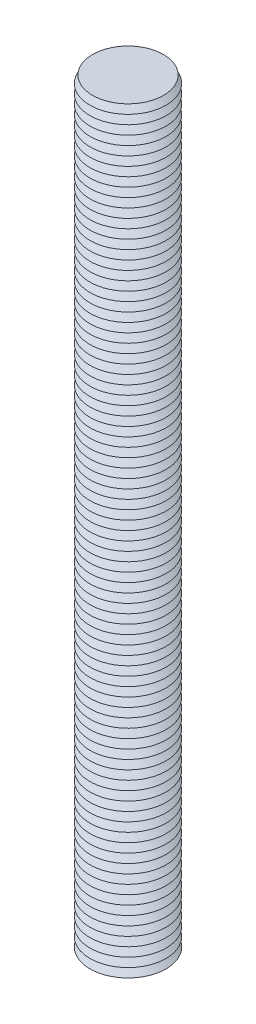
SolidWorks part; units mm, degrees
ref_plane "前视基准面" through (0, 0, 0) normal (0, 0, 1) x (1, 0, 0)
ref_plane "上视基准面" through (0, 0, 0) normal (0, 1, 0) x (1, 0, 0)
ref_plane "右视基准面" through (0, 0, 0) normal (1, 0, 0) x (0, 0, -1)
sketch "草图1" plane through (0, 0, 0) normal (0, 0, 1) x (1, 0, 0)
  line B0 (0, 0) -> (0, 80)
  line B1 (3.3, 0) -> (0, 0)
  line B2 (4, 0.4744) -> (3.3, 0)
  line B3 (0, 80) -> (3.7341, 80)
  line B4 (4, 0.4744) -> (3.3, 0.9489)
  line B5 (4, 1.4233) -> (3.3, 0.9489)
  line B6 (4, 1.4233) -> (3.3, 1.8978)
  line B7 (4, 2.3722) -> (3.3, 1.8978)
  line B8 (4, 2.3722) -> (3.3, 2.8466)
  line B9 (4, 3.3211) -> (3.3, 2.8466)
  line B10 (4, 3.3211) -> (3.3, 3.7955)
  line B11 (4, 4.27) -> (3.3, 3.7955)
  line B12 (4, 4.27) -> (3.3, 4.7444)
  line B13 (4, 5.2188) -> (3.3, 4.7444)
  line B14 (4, 5.2188) -> (3.3, 5.6933)
  line B15 (4, 6.1677) -> (3.3, 5.6933)
  line B16 (4, 6.1677) -> (3.3, 6.6421)
  line B17 (4, 7.1166) -> (3.3, 6.6421)
  line B18 (4, 7.1166) -> (3.3, 7.591)
  line B19 (4, 8.0655) -> (3.3, 7.591)
  line B20 (4, 8.0655) -> (3.3, 8.5399)
  line B21 (4, 9.0143) -> (3.3, 8.5399)
  line B22 (4, 9.0143) -> (3.3, 9.4888)
  line B23 (4, 9.9632) -> (3.3, 9.4888)
  line B24 (4, 9.9632) -> (3.3, 10.4377)
  line B25 (4, 10.9121) -> (3.3, 10.4377)
  line B26 (4, 10.9121) -> (3.3, 11.3865)
  line B27 (4, 11.861) -> (3.3, 11.3865)
  line B28 (4, 11.861) -> (3.3, 12.3354)
  line B29 (4, 12.8099) -> (3.3, 12.3354)
  line B30 (4, 12.8099) -> (3.3, 13.2843)
  line B31 (4, 13.7587) -> (3.3, 13.2843)
  line B32 (4, 13.7587) -> (3.3, 14.2332)
  line B33 (4, 14.7076) -> (3.3, 14.2332)
  line B34 (4, 14.7076) -> (3.3, 15.1821)
  line B35 (4, 15.6565) -> (3.3, 15.1821)
  line B36 (4, 15.6565) -> (3.3, 16.1309)
  line B37 (4, 16.6054) -> (3.3, 16.1309)
  line B38 (4, 16.6054) -> (3.3, 17.0798)
  line B39 (4, 17.5542) -> (3.3, 17.0798)
  line B40 (4, 17.5542) -> (3.3, 18.0287)
  line B41 (4, 18.5031) -> (3.3, 18.0287)
  line B42 (4, 18.5031) -> (3.3, 18.9776)
  line B43 (4, 19.452) -> (3.3, 18.9776)
  line B44 (4, 19.452) -> (3.3, 19.9264)
  line B45 (4, 20.4009) -> (3.3, 19.9264)
  line B46 (4, 20.4009) -> (3.3, 20.8753)
  line B47 (4, 21.3498) -> (3.3, 20.8753)
  line B48 (4, 21.3498) -> (3.3, 21.8242)
  line B49 (4, 22.2986) -> (3.3, 21.8242)
  line B50 (4, 22.2986) -> (3.3, 22.7731)
  line B51 (4, 23.2475) -> (3.3, 22.7731)
  line B52 (4, 23.2475) -> (3.3, 23.722)
  line B53 (4, 24.1964) -> (3.3, 23.722)
  line B54 (4, 24.1964) -> (3.3, 24.6708)
  line B55 (4, 25.1453) -> (3.3, 24.6708)
  line B56 (4, 25.1453) -> (3.3, 25.6197)
  line B57 (4, 26.0942) -> (3.3, 25.6197)
  line B58 (4, 26.0942) -> (3.3, 26.5686)
  line B59 (4, 27.043) -> (3.3, 26.5686)
  line B60 (4, 27.043) -> (3.3, 27.5175)
  line B61 (4, 27.9919) -> (3.3, 27.5175)
  line B62 (4, 27.9919) -> (3.3, 28.4663)
  line B63 (4, 28.9408) -> (3.3, 28.4663)
  line B64 (4, 28.9408) -> (3.3, 29.4152)
  line B65 (4, 29.8897) -> (3.3, 29.4152)
  line B66 (4, 29.8897) -> (3.3, 30.3641)
  line B67 (4, 30.8385) -> (3.3, 30.3641)
  line B68 (4, 30.8385) -> (3.3, 31.313)
  line B69 (4, 31.7874) -> (3.3, 31.313)
  line B70 (4, 31.7874) -> (3.3, 32.2619)
  line B71 (4, 32.7363) -> (3.3, 32.2619)
  line B72 (4, 32.7363) -> (3.3, 33.2107)
  line B73 (4, 33.6852) -> (3.3, 33.2107)
  line B74 (4, 33.6852) -> (3.3, 34.1596)
  line B75 (4, 34.6341) -> (3.3, 34.1596)
  line B76 (4, 34.6341) -> (3.3, 35.1085)
  line B77 (4, 35.5829) -> (3.3, 35.1085)
  line B78 (4, 35.5829) -> (3.3, 36.0574)
  line B79 (4, 36.5318) -> (3.3, 36.0574)
  line B80 (4, 36.5318) -> (3.3, 37.0063)
  line B81 (4, 37.4807) -> (3.3, 37.0063)
  line B82 (4, 37.4807) -> (3.3, 37.9551)
  line B83 (4, 38.4296) -> (3.3, 37.9551)
  line B84 (4, 38.4296) -> (3.3, 38.904)
  line B85 (4, 39.3785) -> (3.3, 38.904)
  line B86 (4, 39.3785) -> (3.3, 39.8529)
  line B87 (4, 40.3273) -> (3.3, 39.8529)
  line B88 (4, 40.3273) -> (3.3, 40.8018)
  line B89 (4, 41.2762) -> (3.3, 40.8018)
  line B90 (4, 41.2762) -> (3.3, 41.7506)
  line B91 (4, 42.2251) -> (3.3, 41.7506)
  line B92 (4, 42.2251) -> (3.3, 42.6995)
  line B93 (4, 43.174) -> (3.3, 42.6995)
  line B94 (4, 43.174) -> (3.3, 43.6484)
  line B95 (4, 44.1228) -> (3.3, 43.6484)
  line B96 (4, 44.1228) -> (3.3, 44.5973)
  line B97 (4, 45.0717) -> (3.3, 44.5973)
  line B98 (4, 45.0717) -> (3.3, 45.5462)
  line B99 (4, 46.0206) -> (3.3, 45.5462)
  line B100 (4, 46.0206) -> (3.3, 46.495)
  line B101 (4, 46.9695) -> (3.3, 46.495)
  line B102 (4, 46.9695) -> (3.3, 47.4439)
  line B103 (4, 47.9184) -> (3.3, 47.4439)
  line B104 (4, 47.9184) -> (3.3, 48.3928)
  line B105 (4, 48.8672) -> (3.3, 48.3928)
  line B106 (4, 48.8672) -> (3.3, 49.3417)
  line B107 (4, 49.8161) -> (3.3, 49.3417)
  line B108 (4, 49.8161) -> (3.3, 50.2906)
  line B109 (4, 50.765) -> (3.3, 50.2906)
  line B110 (4, 50.765) -> (3.3, 51.2394)
  line B111 (4, 51.7139) -> (3.3, 51.2394)
  line B112 (4, 51.7139) -> (3.3, 52.1883)
  line B113 (4, 52.6627) -> (3.3, 52.1883)
  line B114 (4, 52.6627) -> (3.3, 53.1372)
  line B115 (4, 53.6116) -> (3.3, 53.1372)
  line B116 (4, 53.6116) -> (3.3, 54.0861)
  line B117 (4, 54.5605) -> (3.3, 54.0861)
  line B118 (4, 54.5605) -> (3.3, 55.0349)
  line B119 (4, 55.5094) -> (3.3, 55.0349)
  line B120 (4, 55.5094) -> (3.3, 55.9838)
  line B121 (4, 56.4583) -> (3.3, 55.9838)
  line B122 (4, 56.4583) -> (3.3, 56.9327)
  line B123 (4, 57.4071) -> (3.3, 56.9327)
  line B124 (4, 57.4071) -> (3.3, 57.8816)
  line B125 (4, 58.356) -> (3.3, 57.8816)
  line B126 (4, 58.356) -> (3.3, 58.8305)
  line B127 (4, 59.3049) -> (3.3, 58.8305)
  line B128 (4, 59.3049) -> (3.3, 59.7793)
  line B129 (4, 60.2538) -> (3.3, 59.7793)
  line B130 (4, 60.2538) -> (3.3, 60.7282)
  line B131 (4, 61.2027) -> (3.3, 60.7282)
  line B132 (4, 61.2027) -> (3.3, 61.6771)
  line B133 (4, 62.1515) -> (3.3, 61.6771)
  line B134 (4, 62.1515) -> (3.3, 62.626)
  line B135 (4, 63.1004) -> (3.3, 62.626)
  line B136 (4, 63.1004) -> (3.3, 63.5748)
  line B137 (4, 64.0493) -> (3.3, 63.5748)
  line B138 (4, 64.0493) -> (3.3, 64.5237)
  line B139 (4, 64.9982) -> (3.3, 64.5237)
  line B140 (4, 64.9982) -> (3.3, 65.4726)
  line B141 (4, 65.947) -> (3.3, 65.4726)
  line B142 (4, 65.947) -> (3.3, 66.4215)
  line B143 (4, 66.8959) -> (3.3, 66.4215)
  line B144 (4, 66.8959) -> (3.3, 67.3704)
  line B145 (4, 67.8448) -> (3.3, 67.3704)
  line B146 (4, 67.8448) -> (3.3, 68.3192)
  line B147 (4, 68.7937) -> (3.3, 68.3192)
  line B148 (4, 68.7937) -> (3.3, 69.2681)
  line B149 (4, 69.7426) -> (3.3, 69.2681)
  line B150 (4, 69.7426) -> (3.3, 70.217)
  line B151 (4, 70.6914) -> (3.3, 70.217)
  line B152 (4, 70.6914) -> (3.3, 71.1659)
  line B153 (4, 71.6403) -> (3.3, 71.1659)
  line B154 (4, 71.6403) -> (3.3, 72.1148)
  line B155 (4, 72.5892) -> (3.3, 72.1148)
  line B156 (4, 72.5892) -> (3.3, 73.0636)
  line B157 (4, 73.5381) -> (3.3, 73.0636)
  line B158 (4, 73.5381) -> (3.3, 74.0125)
  line B159 (4, 74.4869) -> (3.3, 74.0125)
  line B160 (4, 74.4869) -> (3.3, 74.9614)
  line B161 (4, 75.4358) -> (3.3, 74.9614)
  line B162 (4, 75.4358) -> (3.3, 75.9103)
  line B163 (4, 76.3847) -> (3.3, 75.9103)
  line B164 (4, 76.3847) -> (3.3, 76.8591)
  line B165 (4, 77.3336) -> (3.3, 76.8591)
  line B166 (4, 77.3336) -> (3.3, 77.808)
  line B167 (4, 78.2825) -> (3.3, 77.808)
  line B168 (4, 78.2825) -> (3.3, 78.7569)
  line B169 (4, 79.2313) -> (3.3, 78.7569)
  line B170 (4, 79.2313) -> (3.3, 79.7058)
  line B171 (3.7341, 80) -> (3.3, 79.7058)
sketch_block_instance "A$C1230774F-1"
sketch_block "A$C1230774F"
revolve "旋转1" add sketch "草图1" angle 360 about L0
